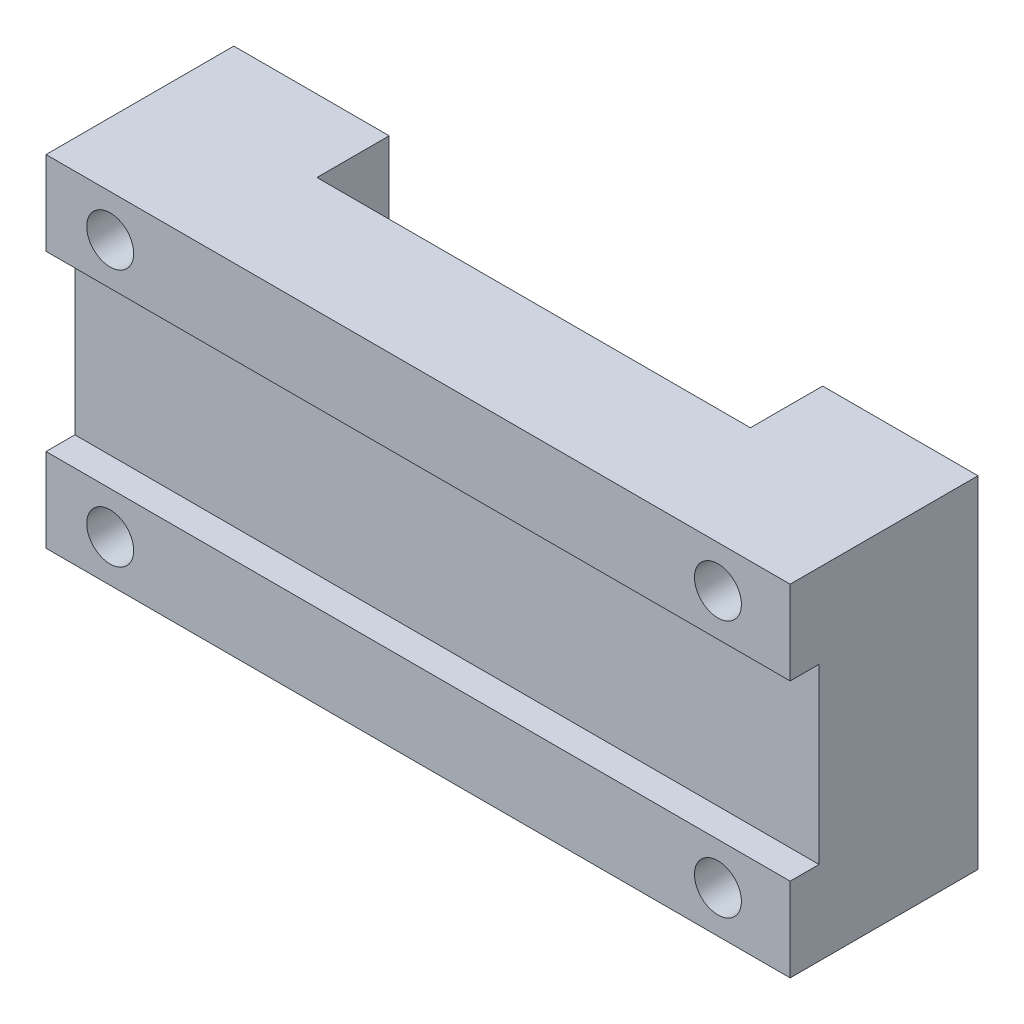
SolidWorks part; units mm, degrees
ref_plane "Alzado" through (0, 0, 0) normal (0, 0, 1) x (1, 0, 0)
ref_plane "Planta" through (0, 0, 0) normal (0, 1, 0) x (1, 0, 0)
ref_plane "Vista lateral" through (0, 0, 0) normal (1, 0, 0) x (0, 0, -1)
sketch "Croquis2" plane through (0, 0, 0) normal (0, 0, 1) x (1, 0, 0)
  line L24 (25.3, 14) -> (25.3, 8.2) construction
  line L48 (18.3, 14) -> (32.3, 14) construction
  line L56 (24, 8.2) -> (75.5028, 8.2)
  line L63 (24, 42) -> (24, 6) construction
  line L64 (75.5028, 6) -> (75.5028, 42.5) construction
  line L65 (74.7, 26) -> (74.7, 31.8) construction
  line L66 (81.7, 26) -> (67.7, 26) construction
  line L67 (24, 31.8) -> (24, 8.2)
  line L68 (24, 31.8) -> (75.5028, 31.8)
  line L69 (75.5028, 31.8) -> (75.5028, 8.2)
  dimension "D1" = 8.2
extrude "Saliente-Extruir1" add sketch "Croquis2" along normal up to vertex (11 mm away)
sketch "Croquis4" plane through (75.5028, 0, 0) normal (1, 0, 0) x (0, 0, -1)
  line L0 (-11, 8.2) -> (-13, 8.2)
  line L1 (-13, 8.2) -> (-13, 14)
  line L2 (-11, 8.2) -> (-11, 14)
  line L3 (-11, 31.8) -> (-13, 31.8)
  line L4 (-13, 31.8) -> (-13, 26)
  line L5 (-11, 26) -> (-11, 31.8)
  line L6 (0, 8.2) -> (0, 31.8) construction
  line L7 (-11, 31.8) -> (0, 31.8) construction
  line L8 (-13, 14) -> (-11, 14)
  line L10 (-13, 26) -> (-11, 26)
  dimension "D1" = 5.8
  dimension "D8" = 13
extrude "Saliente-Extruir2" add sketch "Croquis4" against normal up to vertex (51.5028 mm away)
sketch "Croquis5" plane through (0, 8.2, 0) normal (0, -1, 0) x (1, 0, 0)
  line L0 (75.5028, 13) -> (75.5028, 0) construction
  line L2 (24, 0) -> (75.5028, 0) construction
  line L3 (49.7514, 0) -> (34.7514, 0)
  line L5 (49.7514, 5) -> (34.7514, 5)
  line L6 (34.7514, 0) -> (34.7514, 5)
  line L7 (49.7514, 0) -> (64.7514, 0)
  line L9 (49.7514, 5) -> (64.7514, 5)
  line L10 (64.7514, 0) -> (64.7514, 5)
  dimension "D1" = 10.7514
  dimension "D2" = 5
extrude "Cortar-Extruir1" cut sketch "Croquis5" against normal up to vertex
sketch "Croquis6" plane through (0, 0, 13) normal (0, 0, 1) x (1, 0, 0)
  circle A0 centre (28.4426, 11.1) radius 1.625
  circle A1 centre (28.4426, 28.9) radius 1.625
  circle A2 centre (70.5028, 11.1) radius 1.625
  circle A3 centre (70.5028, 28.9) radius 1.625
  dimension "D1" = 3.25
extrude "Cortar-Extruir2" cut sketch "Croquis6" against normal up to vertex
